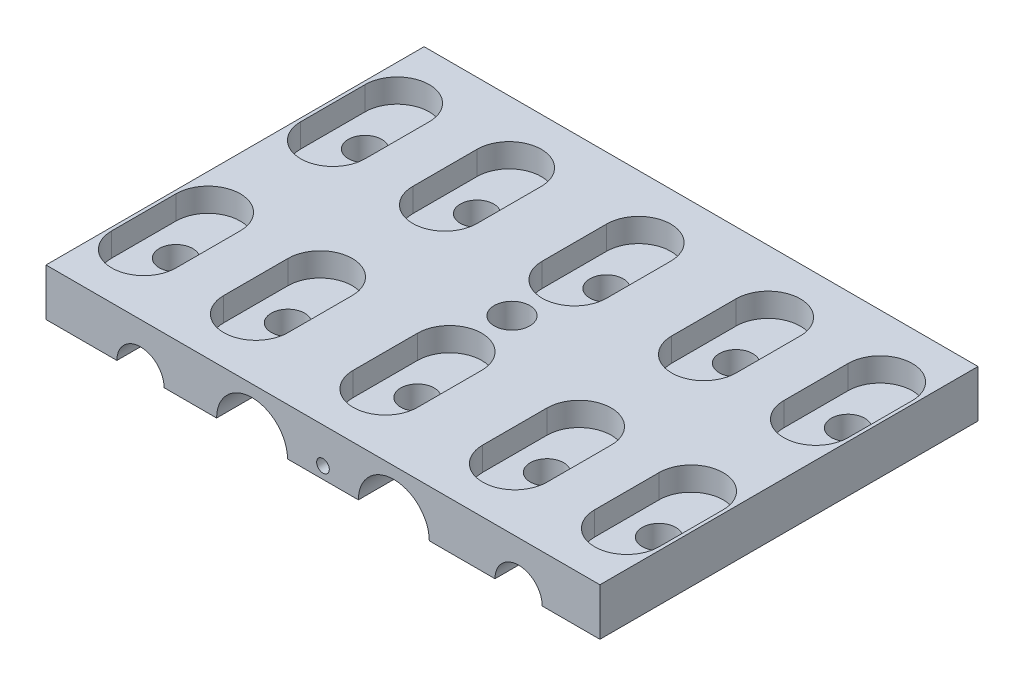
SolidWorks part; units mm, degrees
material "Copper"
ref_plane "Front Plane" through (0, 0, 0) normal (0, 0, 1) x (1, 0, 0)
ref_plane "Top Plane" through (0, 0, 0) normal (0, 1, 0) x (1, 0, 0)
ref_plane "Right Plane" through (0, 0, 0) normal (1, 0, 0) x (0, 0, -1)
sketch "Sketch1" plane through (0, 0, 0) normal (0, 1, 0) x (1, 0, 0)
  line L1 (-37.211, 25.4) -> (37.211, 25.4)
  line L2 (-37.211, 25.4) -> (-37.211, -25.4)
  line L3 (-37.211, -25.4) -> (37.211, -25.4)
  line L4 (37.211, 25.4) -> (37.211, -25.4)
  dimension "D1" = 50.8
  dimension "D2" = 74.422
  dimension "D3" = 37.211
  dimension "D4" = 25.4
extrude "Boss-Extrude1" add sketch "Sketch1" along normal blind 6.35
sketch "Sketch2" plane through (0, 0, 25.4) normal (0, 0, 1) x (1, 0, 0)
  line L0 (-37.211, 0) -> (37.211, 0) construction
  line L1 (-37.211, 6.35) -> (-37.211, 0) construction
  circle A0 centre (-24.511, 0) radius 3.175
  circle A1 centre (26.289, 0) radius 3.175
  dimension "D3" = 6.35
  dimension "D1" = 50.8
  dimension "D2" = 12.7
extrude "Cut-Extrude1" cut sketch "Sketch2" against normal through all
sketch "Sketch3" plane through (0, 0, 25.4) normal (0, 0, 1) x (1, 0, 0)
  line L0 (-21.336, 0) -> (23.114, 0) construction
  circle A0 centre (-9.525, 0) radius 4.7625
  circle A1 centre (9.525, 0) radius 4.7625
  dimension "D1" = 9.525
  dimension "D2" = 19.05
  dimension "D3" = 9.525
extrude "Cut-Extrude2" cut sketch "Sketch3" against normal through all
hole_wizard "#8 Clearance Hole1" positions "Sketch5" profile "Sketch4" hole size "#8" standard "ANSI Inch" end condition through all
sketch "Sketch5" plane through (0, 6.35, 0) normal (0, 1, 0) x (1, 0, 0)
  line L2 (37.211, 25.4) -> (-37.211, 25.4) construction
  line L3 (-37.211, -25.4) -> (37.211, -25.4) construction
  line L4 (-37.211, 25.4) -> (-37.211, -25.4) construction
  line L5 (37.211, -25.4) -> (37.211, 25.4) construction
  point P0 (-32.4485, 12.7)
  point P2 (-32.4485, -12.7)
  point P4 (-17.399, -12.7)
  point P6 (0, -12.7)
  point P8 (17.399, -12.7)
  point P10 (32.4485, -12.7)
  point P12 (32.4485, 12.7)
  point P14 (17.399, 12.7)
  point P16 (0, 12.7)
  point P18 (-17.399, 12.7)
  dimension "D1" = 12.7
  dimension "D2" = 12.7
  dimension "D3" = 4.7625
  dimension "D4" = 4.7625
  dimension "D5" = 19.812
  dimension "D6" = 19.812
sketch "Sketch4" plane through (-32.4485, 6.35, -12.7) normal (1, 0, 0) x (0, 0, 1)
  line L0 (0, 0) -> (0, 6.35)
  line L1 (0, 6.35) -> (2.2479, 6.35)
  line L2 (2.2479, 6.35) -> (2.2479, 0)
  line L5 (2.2479, 0) -> (0, 0)
  line L11 (0, -6.35) -> (0, 107.95) construction
  dimension "Thru Hole Dia." = 4.4958
  dimension "Thru Hole Depth" = 6.35
sketch "Sketch6" plane through (0, 6.35, 0) normal (0, 1, 0) x (1, 0, 0)
  line L0 (-17.399, 17.018) -> (-17.399, 8.382) construction
  line L1 (-13.081, 17.018) -> (-13.081, 8.382)
  line L2 (-21.717, 17.018) -> (-21.717, 8.382)
  line L3 (0, 25.4) -> (0, 0) construction
  line L4 (37.211, 25.4) -> (-37.211, 25.4) construction
  line L5 (37.211, 0) -> (0, 0) construction
  line L6 (37.211, -25.4) -> (37.211, 25.4) construction
  line L7 (17.399, 17.018) -> (17.399, 8.382) construction
  line L8 (13.081, 17.018) -> (13.081, 8.382)
  line L9 (21.717, 17.018) -> (21.717, 8.382)
  line L10 (17.399, -17.018) -> (17.399, -8.382) construction
  line L11 (13.081, -17.018) -> (13.081, -8.382)
  line L12 (21.717, -17.018) -> (21.717, -8.382)
  line L13 (-17.399, -17.018) -> (-17.399, -8.382) construction
  line L14 (-13.081, -17.018) -> (-13.081, -8.382)
  line L15 (-21.717, -17.018) -> (-21.717, -8.382)
  line L16 (0, 17.018) -> (0, 8.382) construction
  line L17 (4.318, 17.018) -> (4.318, 8.382)
  line L18 (-4.318, 17.018) -> (-4.318, 8.382)
  line L19 (0, -17.018) -> (0, -8.382) construction
  line L20 (4.318, -17.018) -> (4.318, -8.382)
  line L21 (-4.318, -17.018) -> (-4.318, -8.382)
  line L22 (-32.4485, 17.018) -> (-32.4485, 8.382) construction
  line L23 (-28.1305, 17.018) -> (-28.1305, 8.382)
  line L24 (-36.7665, 17.018) -> (-36.7665, 8.382)
  line L25 (-32.4485, -17.018) -> (-32.4485, -8.382) construction
  line L26 (-28.1305, -17.018) -> (-28.1305, -8.382)
  line L27 (-36.7665, -17.018) -> (-36.7665, -8.382)
  line L28 (32.4485, 17.018) -> (32.4485, 8.382) construction
  line L29 (28.1305, 17.018) -> (28.1305, 8.382)
  line L30 (36.7665, 17.018) -> (36.7665, 8.382)
  line L31 (32.4485, -17.018) -> (32.4485, -8.382) construction
  line L32 (28.1305, -17.018) -> (28.1305, -8.382)
  line L33 (36.7665, -17.018) -> (36.7665, -8.382)
  arc A0 (-13.081, 17.018) -> (-21.717, 17.018) centre (-17.399, 17.018) ccw
  arc A1 (-21.717, 8.382) -> (-13.081, 8.382) centre (-17.399, 8.382) ccw
  arc A2 (13.081, 17.018) -> (21.717, 17.018) centre (17.399, 17.018) cw
  arc A3 (21.717, 8.382) -> (13.081, 8.382) centre (17.399, 8.382) cw
  arc A4 (13.081, -17.018) -> (21.717, -17.018) centre (17.399, -17.018) ccw
  arc A5 (21.717, -8.382) -> (13.081, -8.382) centre (17.399, -8.382) ccw
  arc A6 (-13.081, -17.018) -> (-21.717, -17.018) centre (-17.399, -17.018) cw
  arc A7 (-21.717, -8.382) -> (-13.081, -8.382) centre (-17.399, -8.382) cw
  arc A11 (4.318, 17.018) -> (-4.318, 17.018) centre (0, 17.018) ccw
  arc A12 (-4.318, 8.382) -> (4.318, 8.382) centre (0, 8.382) ccw
  arc A13 (4.318, -17.018) -> (-4.318, -17.018) centre (0, -17.018) cw
  arc A14 (-4.318, -8.382) -> (4.318, -8.382) centre (0, -8.382) cw
  arc A15 (-28.1305, 17.018) -> (-36.7665, 17.018) centre (-32.4485, 17.018) ccw
  arc A16 (-36.7665, 8.382) -> (-28.1305, 8.382) centre (-32.4485, 8.382) ccw
  arc A17 (-28.1305, -17.018) -> (-36.7665, -17.018) centre (-32.4485, -17.018) cw
  arc A18 (-36.7665, -8.382) -> (-28.1305, -8.382) centre (-32.4485, -8.382) cw
  arc A19 (28.1305, 17.018) -> (36.7665, 17.018) centre (32.4485, 17.018) cw
  arc A20 (36.7665, 8.382) -> (28.1305, 8.382) centre (32.4485, 8.382) cw
  arc A21 (28.1305, -17.018) -> (36.7665, -17.018) centre (32.4485, -17.018) ccw
  arc A22 (36.7665, -8.382) -> (28.1305, -8.382) centre (32.4485, -8.382) ccw
  point P3 (-17.399, 12.7)
  point P18 (17.399, 12.7)
  point P25 (17.399, -12.7)
  point P32 (-17.399, -12.7)
  point P39 (0, 12.7)
  point P46 (0, -12.7)
  point P54 (-32.4485, 12.7)
  point P61 (-32.4485, -12.7)
  point P68 (32.4485, 12.7)
  point P75 (32.4485, -12.7)
  dimension "D1" = 8.636
  dimension "D2" = 12.7
  dimension "D3" = 8.636
  dimension "D4" = 12.7
  dimension "D5" = 8.636
  dimension "D6" = 8.636
  dimension "D7" = 12.7
  dimension "D8" = 8.636
  dimension "D9" = 8.636
extrude "Cut-Extrude3" cut sketch "Sketch6" against normal blind 3.175
sketch "Sketch7" plane through (0, 6.35, 0) normal (0, 1, 0) x (1, 0, 0)
  circle A0 centre (0, 0) radius 2.3813
  dimension "D1" = 4.7625
extrude "Cut-Extrude4" cut sketch "Sketch7" against normal through all
sketch "Sketch8" plane through (0, 0, 25.4) normal (0, 0, 1) x (1, 0, 0)
  line L0 (-4.7625, 0) -> (4.7625, 0) construction
  circle A0 centre (0, 1.5875) radius 0.8509
  dimension "D2" = 1.7018
  dimension "D1" = 1.5875
extrude "Cut-Extrude5" cut sketch "Sketch8" against normal blind 9.525
